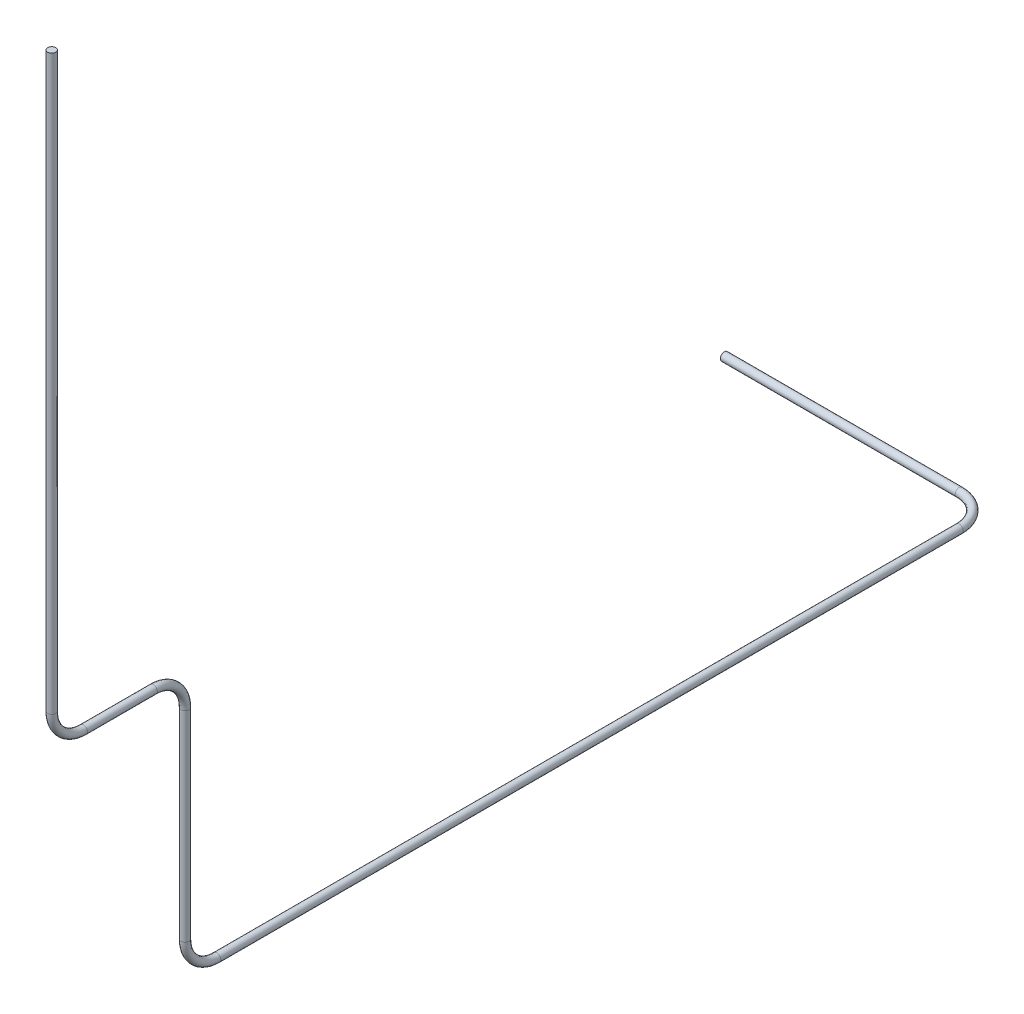
SolidWorks part; units mm, degrees
ref_plane "Alzado" through (0, 0, 0) normal (0, 0, 1) x (1, 0, 0)
ref_plane "Planta" through (0, 0, 0) normal (0, 1, 0) x (1, 0, 0)
ref_plane "Vista lateral" through (0, 0, 0) normal (1, 0, 0) x (0, 0, -1)
sketch3d "Croquis3D1"
  line L3 (656.3772, -1278.8107, 2027.32) -> (1026.3772, -1278.8107, 2027.32)
  line L4 (1076.3772, -1278.8107, 2077.32) -> (1076.3772, -1278.8107, 3246.8796)
  line L5 (1076.3772, -1228.8107, 3296.8796) -> (1076.3772, -912.8847, 3296.8796)
  line L6 (1076.3772, -862.8847, 3346.8796) -> (1076.3772, -862.8847, 3456.8796)
  line L7 (1076.3772, -812.8847, 3506.8796) -> (1076.3772, 89.0414, 3506.8796)
  arc A1 (1026.3772, -1278.8107, 2027.32) -> (1076.3772, -1278.8107, 2077.32) centre (1026.3772, -1278.8107, 2077.32) ccw
  arc A2 (1076.3772, -1278.8107, 3246.8796) -> (1076.3772, -1228.8107, 3296.8796) centre (1076.3772, -1228.8107, 3246.8796) ccw
  arc A3 (1076.3772, -862.8847, 3456.8796) -> (1076.3772, -812.8847, 3506.8796) centre (1076.3772, -812.8847, 3456.8796) ccw
  arc A4 (1076.3772, -912.8847, 3296.8796) -> (1076.3772, -862.8847, 3346.8796) centre (1076.3772, -912.8847, 3346.8796) ccw
  point P4 (1076.3772, -1278.8107, 2027.32)
  point P6 (1026.3772, -1328.8107, 2077.32)
  point P9 (1076.3772, -1278.8107, 3296.8796)
  point P14 (1026.3772, -1228.8107, 3246.8796)
  point P17 (1076.3772, -862.8847, 3506.8796)
  point P18 (1026.3772, -812.8847, 3456.8796)
  point P21 (1076.3772, -862.8847, 3296.8796)
  point P22 (1126.3772, -912.8847, 3346.8796)
  dimension "D1" = 50
  dimension "D2" = 1269.5596
  dimension "D3" = 415.926
  dimension "D4" = 210
  dimension "D5" = 951.9261
  dimension "D6" = 420
sweep "Barrer2" add path "Croquis3D1" circular profile diameter 12.7 parameters "D3"=12.7
